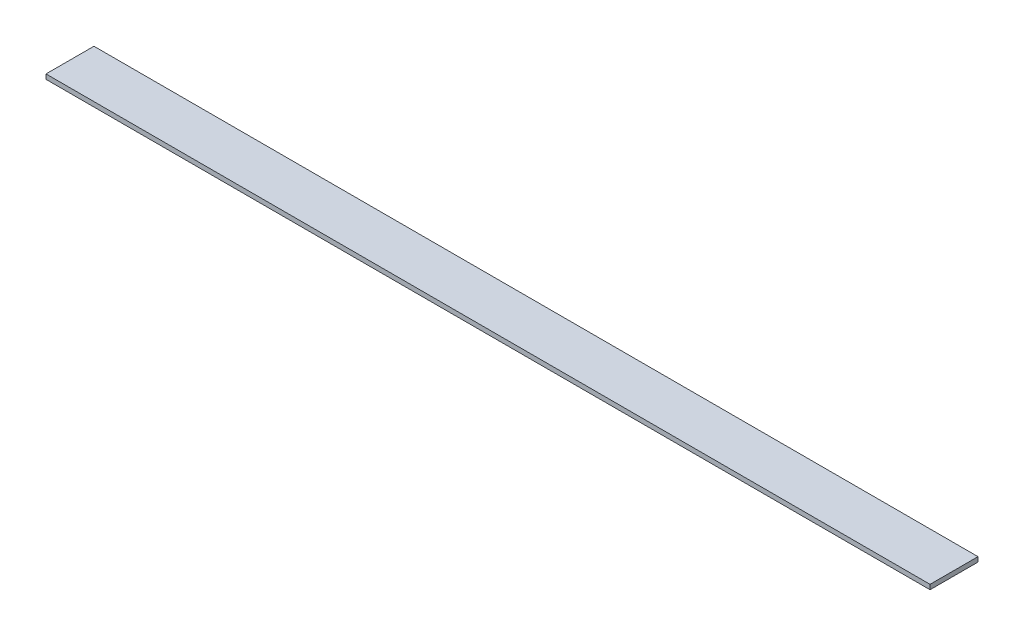
SolidWorks part; units mm, degrees
ref_plane "Front Plane" through (0, 0, 0) normal (0, 0, 1) x (1, 0, 0)
ref_plane "Top Plane" through (0, 0, 0) normal (0, 1, 0) x (1, 0, 0)
ref_plane "Right Plane" through (0, 0, 0) normal (1, 0, 0) x (0, 0, -1)
sketch "Sketch1" plane through (0, 0, 0) normal (0, 1, 0) x (1, 0, 0)
  line L1 (-936.625, 50.8) -> (936.625, 50.8)
  line L2 (-936.625, 50.8) -> (-936.625, -50.8)
  line L3 (-936.625, -50.8) -> (936.625, -50.8)
  line L4 (936.625, 50.8) -> (936.625, -50.8)
  line L5 (-936.625, 50.8) -> (936.625, -50.8) construction
  line L6 (-936.625, -50.8) -> (936.625, 50.8) construction
  point P0 (0, 0)
  dimension "D1" = 1873.25
  dimension "D2" = 101.6
extrude "Boss-Extrude1" add sketch "Sketch1" along normal blind 10
